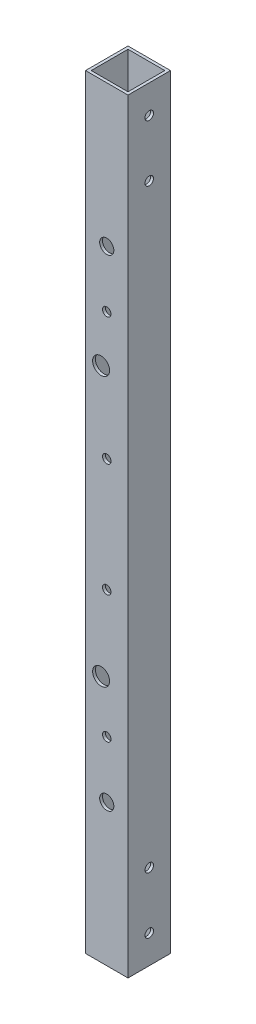
SolidWorks part; units mm, degrees
material "6061-O (SS)"
ref_plane "前视基准面" through (0, 0, 0) normal (0, 0, 1) x (1, 0, 0)
ref_plane "上视基准面" through (0, 0, 0) normal (0, 1, 0) x (1, 0, 0)
ref_plane "右视基准面" through (0, 0, 0) normal (1, 0, 0) x (0, 0, -1)
sketch "草图1" plane through (0, 0, 0) normal (0, 1, 0) x (1, 0, 0)
  line L0 (-6.5, 6.5) -> (6.5, 6.5)
  line L1 (-7.5, -7.5) -> (7.5, -7.5)
  line L2 (-7.5, -7.5) -> (-7.5, 7.5)
  line L3 (-7.5, 7.5) -> (7.5, 7.5)
  line L4 (7.5, -7.5) -> (7.5, 7.5)
  line L5 (-7.5, -7.5) -> (7.5, 7.5) construction
  line L6 (-7.5, 7.5) -> (7.5, -7.5) construction
  line L7 (6.5, -6.5) -> (6.5, 6.5)
  line L8 (-6.5, -6.5) -> (6.5, -6.5)
  line L9 (-6.5, -6.5) -> (-6.5, 6.5)
  point P0 (0, 0)
  dimension "D1" = 15
  dimension "D2" = 1
extrude "凸台-拉伸1" add sketch "草图1" along normal blind 270
sketch "草图2" plane through (0, 0, 7.5) normal (0, 0, 1) x (1, 0, 0)
  line L0 (0, 270) -> (0, 0) construction
  line L1 (-7.5, 270) -> (7.5, 270) construction
  line L2 (-7.5, 135) -> (7.5, 135) construction
  line L3 (-7.5, 270) -> (-7.5, 0) construction
  line L4 (7.5, 270) -> (7.5, 0) construction
  circle A0 centre (0, 155) radius 1.5
  circle A1 centre (0, 115) radius 1.5
  circle A2 centre (0, 200) radius 1.5
  circle A3 centre (0, 70) radius 1.5
  circle A4 centre (0, 220) radius 2.5
  circle A5 centre (0, 50) radius 2.5
  circle A6 centre (-2, 182.5) radius 3
  circle A7 centre (-2, 87.5) radius 3
  dimension "D1" = 40
  dimension "D2" = 45
  dimension "D3" = 3
  dimension "D4" = 170
  dimension "D5" = 5
  dimension "D6" = 95
  dimension "D7" = 6
  dimension "D8" = 2
extrude "切除-拉伸1" cut sketch "草图2" against normal through all
sketch "草图3" plane through (7.5, 0, 0) normal (1, 0, 0) x (0, 0, -1)
  line L0 (0, 270) -> (0, 0) construction
  line L1 (-7.5, 270) -> (7.5, 270) construction
  line L2 (-7.5, 135) -> (7.5, 135) construction
  line L3 (-7.5, 270) -> (-7.5, 0) construction
  line L4 (7.5, 270) -> (7.5, 0) construction
  circle A0 centre (0, 240) radius 1.5
  circle A1 centre (0, 30) radius 1.5
  circle A2 centre (0, 10) radius 1.5
  circle A3 centre (0, 260) radius 1.5
  dimension "D1" = 210
  dimension "D2" = 20
  dimension "D3" = 3
extrude "切除-拉伸2" cut sketch "草图3" against normal through all
